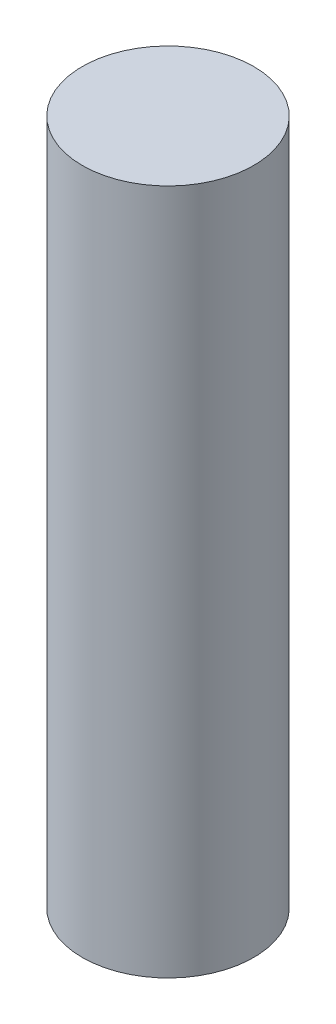
SolidWorks part; units mm, degrees
ref_plane "正面" through (0, 0, 0) normal (0, 0, 1) x (1, 0, 0)
ref_plane "平面" through (0, 0, 0) normal (0, 1, 0) x (1, 0, 0)
ref_plane "右側面" through (0, 0, 0) normal (1, 0, 0) x (0, 0, -1)
sketch "ｽｹｯﾁ1" plane through (0, 0, 0) normal (0, 1, 0) x (1, 0, 0)
  circle A0 centre (0, 0) radius 5
  dimension "D1" = 10
extrude "ﾎﾞｽ - 押し出し1" add sketch "ｽｹｯﾁ1" along normal blind 40 contours A0
